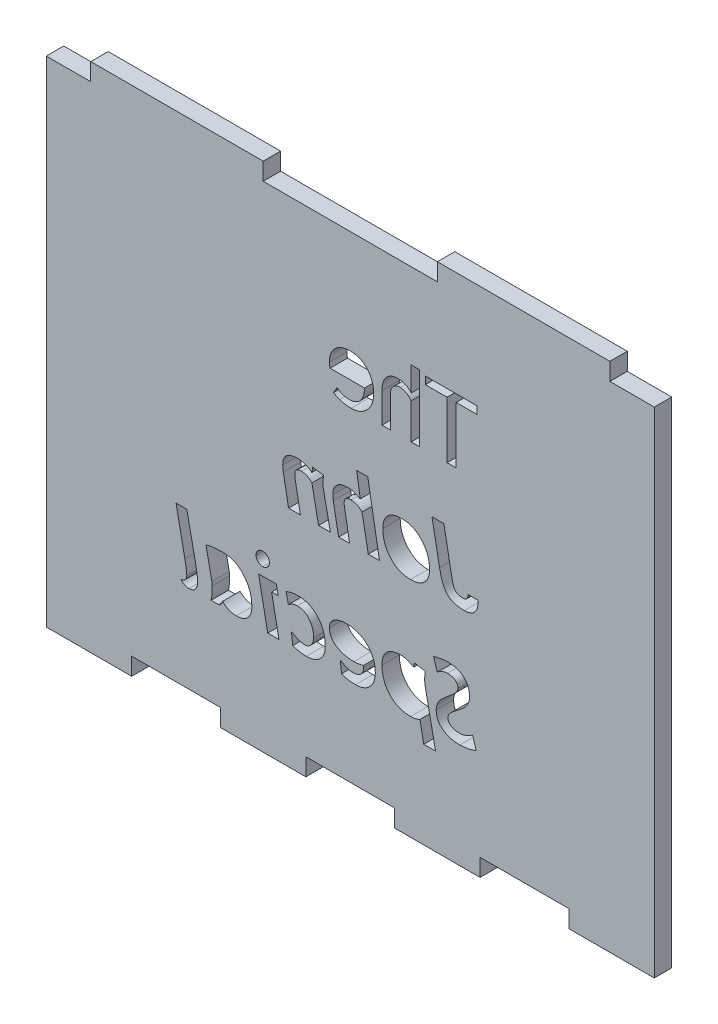
SolidWorks part; units mm, degrees
ref_plane "Front Plane" through (0, 0, 0) normal (0, 0, 1) x (1, 0, 0)
ref_plane "Top Plane" through (0, 0, 0) normal (0, 1, 0) x (1, 0, 0)
ref_plane "Right Plane" through (0, 0, 0) normal (1, 0, 0) x (0, 0, -1)
sketch "Sketch1" plane through (0, 0, 0) normal (0, 0, 1) x (1, 0, 0)
  line L1 (-44.323, 36.0502) -> (44.323, 36.0502)
  line L2 (-44.323, 36.0502) -> (-44.323, -36.0502)
  line L3 (-44.323, -36.0502) -> (44.323, -36.0502)
  line L4 (44.323, 36.0502) -> (44.323, -36.0502)
  line L5 (0, -36.0502) -> (0, 36.0502) construction
  line L6 (-44.323, 0) -> (44.323, 0) construction
  point P0 (0, 0)
  dimension "D1" = 72.1004
  dimension "D2" = 88.646
extrude "Boss-Extrude1" add sketch "Sketch1" along normal blind 2.54
sketch "Sketch2" plane through (0, 0, 2.54) normal (0, 0, 1) x (1, 0, 0)
  line L0 (44.323, 36.0502) -> (-44.323, 36.0502) construction
  line L1 (-37.846, 36.0502) -> (-12.7, 36.0502)
  line L2 (-37.846, 36.0502) -> (-37.846, 38.5902)
  line L3 (-37.846, 38.5902) -> (-12.7, 38.5902)
  line L4 (-12.7, 36.0502) -> (-12.7, 38.5902)
  dimension "D1" = 25.146
  dimension "D2" = 12.7
  dimension "D3" = 2.54
extrude "Boss-Extrude2" add sketch "Sketch2" against normal blind 2.54
mirror "Mirror1" about plane through (0, 0, 0) normal (1, 0, 0) of "Boss-Extrude2"
sketch "Sketch3" plane through (0, 0, 2.54) normal (0, 0, 1) x (1, 0, 0)
  text T0 "The\r\n<b><i>John</i></b>\r\n<b><i>Special</i></b>" font "Trebuchet MS" height in points 36
  point P1 (0, 0)
  point P2 (0, 0)
  point P3 (0, 0)
  point P4 (0, 0)
  point P5 (0, 0)
extrude "Cut-Extrude2" cut sketch "Sketch3" against normal through all
sketch "Sketch4" plane through (0, 0, 0) normal (0, 0, -1) x (-1, 0, 0)
  line L0 (44.323, -36.0502) -> (-44.323, -36.0502) construction
  line L1 (-31.877, -36.0502) -> (-18.923, -36.0502)
  line L2 (-31.877, -36.0502) -> (-31.877, -33.5102)
  line L3 (-31.877, -33.5102) -> (-18.923, -33.5102)
  line L4 (-18.923, -36.0502) -> (-18.923, -33.5102)
  line L6 (-6.477, -36.0502) -> (6.477, -36.0502)
  line L7 (-6.477, -36.0502) -> (-6.477, -33.5102)
  line L8 (-6.477, -33.5102) -> (6.477, -33.5102)
  line L9 (6.477, -36.0502) -> (6.477, -33.5102)
  line L10 (18.923, -36.0502) -> (31.877, -36.0502)
  line L11 (18.923, -36.0502) -> (18.923, -33.5102)
  line L12 (18.923, -33.5102) -> (31.877, -33.5102)
  line L13 (31.877, -36.0502) -> (31.877, -33.5102)
  line L15 (-44.323, -36.0502) -> (-44.323, 36.0502) construction
  point P18 (0, 0)
  point P19 (0, 0)
  dimension "D1" = 25.4
  dimension "D2" = 12.446
  dimension "D3" = 25.4
  dimension "D4" = 25.4
  dimension "D5" = 12.446
  dimension "D6" = 2.54
  dimension "D7" = 12.446
extrude "Cut-Extrude3" cut sketch "Sketch4" against normal through all
